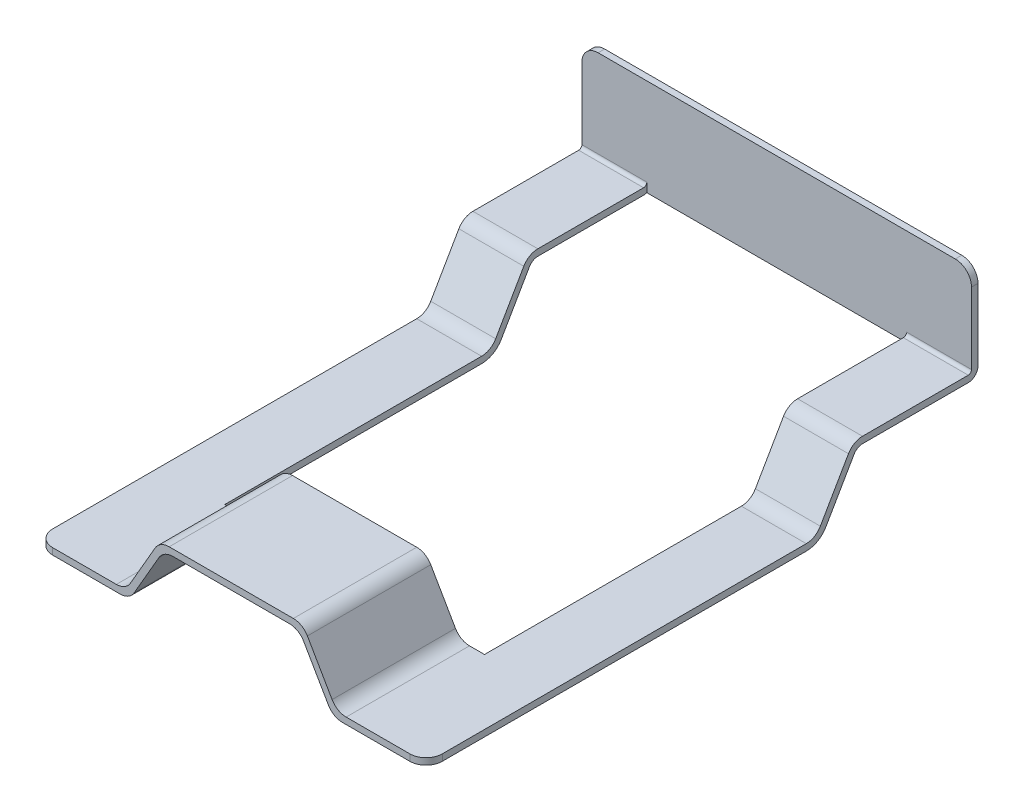
SolidWorks part; units mm, degrees
ref_plane "Front Plane" through (0, 0, 0) normal (0, 0, 1) x (1, 0, 0)
ref_plane "Top Plane" through (0, 0, 0) normal (0, 1, 0) x (1, 0, 0)
ref_plane "Right Plane" through (0, 0, 0) normal (1, 0, 0) x (0, 0, -1)
sketch "Sketch1" plane through (0, 0, 0) normal (1, 0, 0) x (0, 0, -1)
  line L0 (0, 0) -> (2974.6765, 0)
  line L1 (3084.6617, 63.5) -> (3304.6322, 444.5)
  line L2 (3414.6174, 508) -> (4241.8, 508)
  line L3 (4267.2, 533.4) -> (4267.2, 1219.2)
  line L4 (0, -50.8) -> (2974.6765, -50.8)
  line L5 (3128.6558, 38.1) -> (3348.6263, 419.1)
  line L6 (3414.6174, 457.2) -> (4241.8, 457.2)
  line L7 (4318, 533.4) -> (4318, 1219.2)
  line L8 (0, -50.8) -> (0, 0)
  line L9 (4267.2, 1219.2) -> (4318, 1219.2)
  arc A0 (4241.8, 508) -> (4267.2, 533.4) centre (4241.8, 533.4) ccw
  arc A1 (3304.6322, 444.5) -> (3414.6174, 508) centre (3414.6174, 381) cw
  arc A2 (2974.6765, 0) -> (3084.6617, 63.5) centre (2974.6765, 127) ccw
  arc A3 (2974.6765, -50.8) -> (3128.6558, 38.1) centre (2974.6765, 127) ccw
  arc A4 (3348.6263, 419.1) -> (3414.6174, 457.2) centre (3414.6174, 381) cw
  arc A5 (4241.8, 457.2) -> (4318, 533.4) centre (4241.8, 533.4) ccw
  point P13 (3048, 0)
  dimension "D6" = 25.4
  dimension "D9" = 76.2
  dimension "D10" = 127
  dimension "D1" = 4267.2
  dimension "D2" = 1219.2
  dimension "D3" = 508
  dimension "D4" = 120
  dimension "D5" = 3048
  dimension "D8" = 1270
  dimension "D7" = 50.8
extrude "Boss-Extrude1" add sketch "Sketch1" along normal mid plane 3048
sketch "Sketch2" plane through (0, 0, 0) normal (0, 1, 0) x (1, 0, 0)
  line L0 (1524, 4267.2) -> (-1524, 4267.2) construction
  line L1 (-1016, 4267.2) -> (1016, 4267.2)
  line L2 (-1016, 4267.2) -> (-1016, 965.2)
  line L3 (-1016, 965.2) -> (1016, 965.2)
  line L4 (1016, 4267.2) -> (1016, 965.2)
  line L5 (-1524, 4241.8) -> (-1524, 3414.6174) construction
  line L6 (1524, 4241.8) -> (1524, 3414.6174) construction
  dimension "D1" = 3302
  dimension "D2" = 508
  dimension "D3" = 508
  dimension "D4" = 2032
extrude "Cut-Extrude1" cut sketch "Sketch2" against normal through all and the other way through all
sketch "Sketch3" plane through (0, 0, 0) normal (0, 0, 1) x (1, 0, 0)
  line L0 (-825.5, 0) -> (-559.0194, 461.558)
  line L1 (1524, 0) -> (-1524, 0) construction
  line L2 (1016, 461.558) -> (-1016, 461.558) construction
  line L3 (-559.0194, 461.558) -> (559.0194, 461.558)
  line L4 (559.0194, 461.558) -> (825.5, 0)
  line L5 (-766.8412, 0) -> (-529.69, 410.758)
  line L6 (-529.69, 410.758) -> (529.69, 410.758)
  line L7 (529.69, 410.758) -> (766.8412, 0)
  line L8 (-825.5, 0) -> (-766.8412, 0)
  line L9 (766.8412, 0) -> (825.5, 0)
  line L10 (-781.5059, -25.4) -> (-529.69, 410.758) construction
  line L11 (529.69, 410.758) -> (781.5059, -25.4) construction
  point P6 (0, 461.558)
  dimension "D1" = 50.8
  dimension "D2" = 120
  dimension "D3" = 1651
extrude "Boss-Extrude2" add sketch "Sketch3" against normal up to surface (965.2 mm away) up to face at (0, -25.4, -965.2)
sketch "Sketch4" plane through (0, 0, 0) normal (0, 0, 1) x (1, 0, 0)
  line L0 (-766.8412, 0) -> (-796.1706, -50.8)
  line L1 (1524, -50.8) -> (-1524, -50.8) construction
  line L2 (-796.1706, -50.8) -> (796.1706, -50.8)
  line L3 (796.1706, -50.8) -> (766.8412, 0)
  line L4 (529.69, 410.758) -> (766.8412, 0) construction
  line L5 (-766.8412, 0) -> (-529.69, 410.758) construction
  line L6 (-766.8412, 0) -> (766.8412, 0)
extrude "Cut-Extrude2" cut sketch "Sketch4" against normal up to next
fillet "Fillet1" radius 127 8 edges at (796.1706, -50.8, -482.6) (825.5, 0, -482.6) (559.0194, 461.558, -482.6) (529.69, 410.758, -482.6) (-529.69, 410.758, -482.6) (-559.0194, 461.558, -482.6) (-825.5, 0, -482.6) (-796.1706, -50.8, -482.6)
fillet "Fillet2" radius 127 4 edges at (-1524, -25.4, 0) (1524, -25.4, 0) (-1524, 1219.2, -4292.6) (1524, 1219.2, -4292.6)
